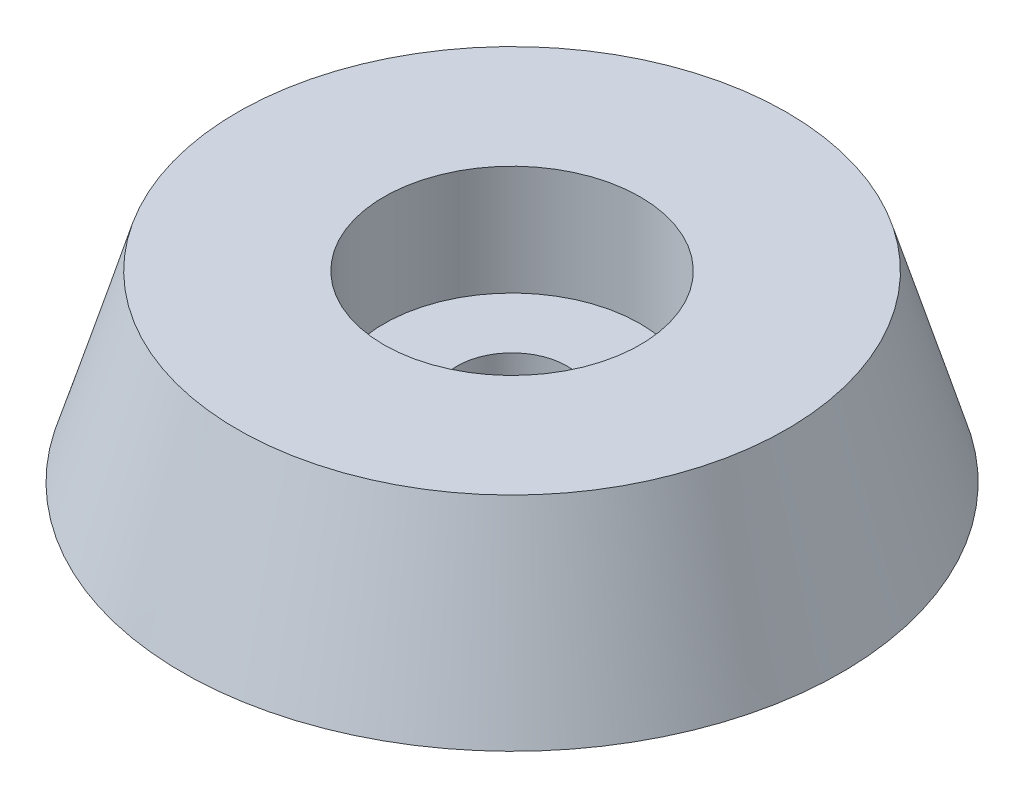
SolidWorks part; units mm, degrees
material "Rubber"
ref_plane "Front Plane" through (0, 0, 0) normal (0, 0, 1) x (1, 0, 0)
ref_plane "Top Plane" through (0, 0, 0) normal (0, 1, 0) x (1, 0, 0)
ref_plane "Right Plane" through (0, 0, 0) normal (1, 0, 0) x (0, 0, -1)
sketch "Sketch1" plane through (0, 0, 0) normal (0, 0, 1) x (1, 0, 0)
  line L0 (0, 0) -> (1.5, 0) construction
  line L1 (1.5, 0) -> (1.5, 2)
  line L2 (1.5, 2) -> (3.5, 2)
  line L3 (3.5, 2) -> (3.5, 5)
  line L4 (3.5, 5) -> (7.5, 5)
  line L5 (7.5, 5) -> (9, 0)
  line L6 (9, 0) -> (1.5, 0)
  line L7 (0, 0) -> (0, 5) construction
  line L8 (0, 5) -> (3.5, 5) construction
  dimension "D1" = 7.5
  dimension "D2" = 9
  dimension "D3" = 1.5
  dimension "D4" = 5
  dimension "D5" = 3.5
  dimension "D6" = 2
revolve "Revolve1" add sketch "Sketch1" angle 360 about L7
